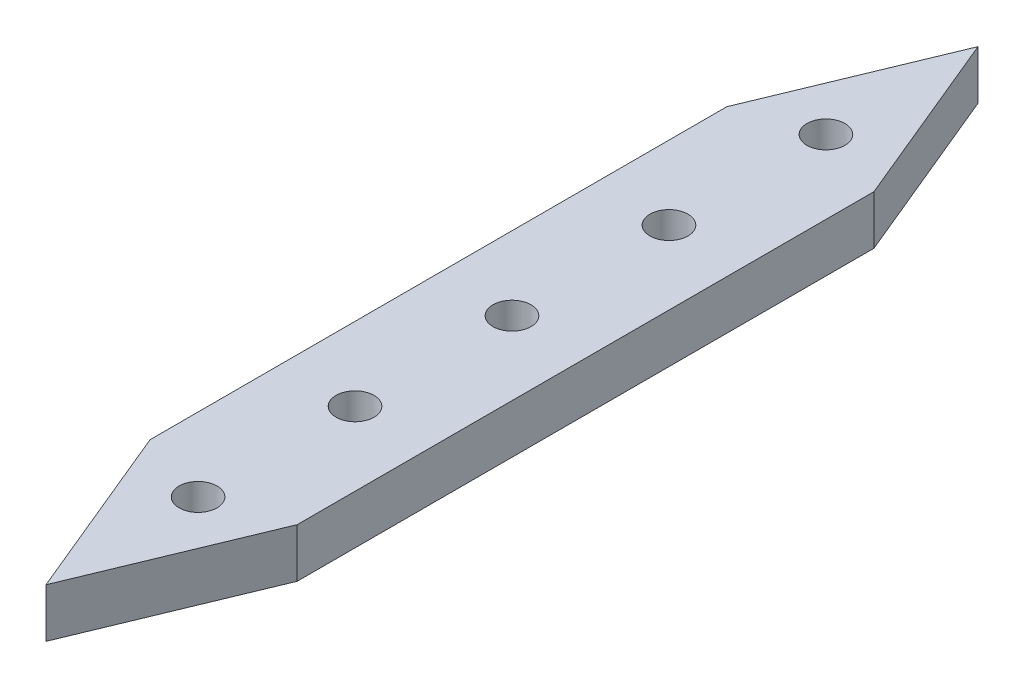
SolidWorks part; units mm, degrees
material "PE Low/Medium Density"
ref_plane "Front Plane" through (0, 0, 0) normal (0, 0, 1) x (1, 0, 0)
ref_plane "Top Plane" through (0, 0, 0) normal (0, 1, 0) x (1, 0, 0)
ref_plane "Right Plane" through (0, 0, 0) normal (1, 0, 0) x (0, 0, -1)
sketch "Sketch1" plane through (0, 0, 0) normal (0, 1, 0) x (1, 0, 0)
  line L0 (0, 60.325) -> (0, -48.1572) construction
  line L1 (0, 60.325) -> (-9.525, 37.3296)
  line L2 (-9.525, 37.3296) -> (-9.525, -37.3296)
  line L3 (-28.5797, 0) -> (23.9031, 0) construction
  line L4 (0, -60.325) -> (-9.525, -37.3296)
  line L5 (0, -60.325) -> (9.525, -37.3296)
  line L6 (9.525, 37.3296) -> (9.525, -37.3296)
  line L7 (0, 60.325) -> (9.525, 37.3296)
  point P9 (-9.525, 0)
  point P10 (9.525, 0)
  dimension "D1" = 19.05
  dimension "D2" = 120.65
  dimension "D3" = 22.5
extrude "Boss-Extrude1" add sketch "Sketch1" along normal blind 6.35
hole_wizard "#10 (0.1935) Diameter Hole1" positions "Sketch4" profile "Sketch5" hole size "#10" standard "ANSI Inch" end condition through all
sketch "Sketch4" plane through (0, 6.35, 0) normal (0, 1, 0) x (1, 0, 0)
  line L0 (-9.525, 0) -> (9.525, 0) construction
  line L1 (-9.525, 37.3296) -> (-9.525, -37.3296) construction
  line L2 (9.525, -37.3296) -> (9.525, 37.3296) construction
  point P0 (0, 20.32)
  point P2 (0, 40.64)
  point P14 (0, 0)
  point P16 (0, -20.32)
  point P18 (0, -40.64)
  dimension "D1" = 20.32
  dimension "D2" = 40.64
  dimension "D3" = 20.32
  dimension "D4" = 40.64
sketch "Sketch5" plane through (0, 6.35, -20.32) normal (1, 0, 0) x (0, 0, 1)
  line L0 (0, 0) -> (0, 6.35)
  line L1 (0, 6.35) -> (2.4574, 6.35)
  line L2 (2.4574, 6.35) -> (2.4574, 0)
  line L5 (2.4574, 0) -> (0, 0)
  line L11 (0, -6.35) -> (0, 107.95) construction
  dimension "Thru Hole Dia." = 4.9149
  dimension "Thru Hole Depth" = 6.35
